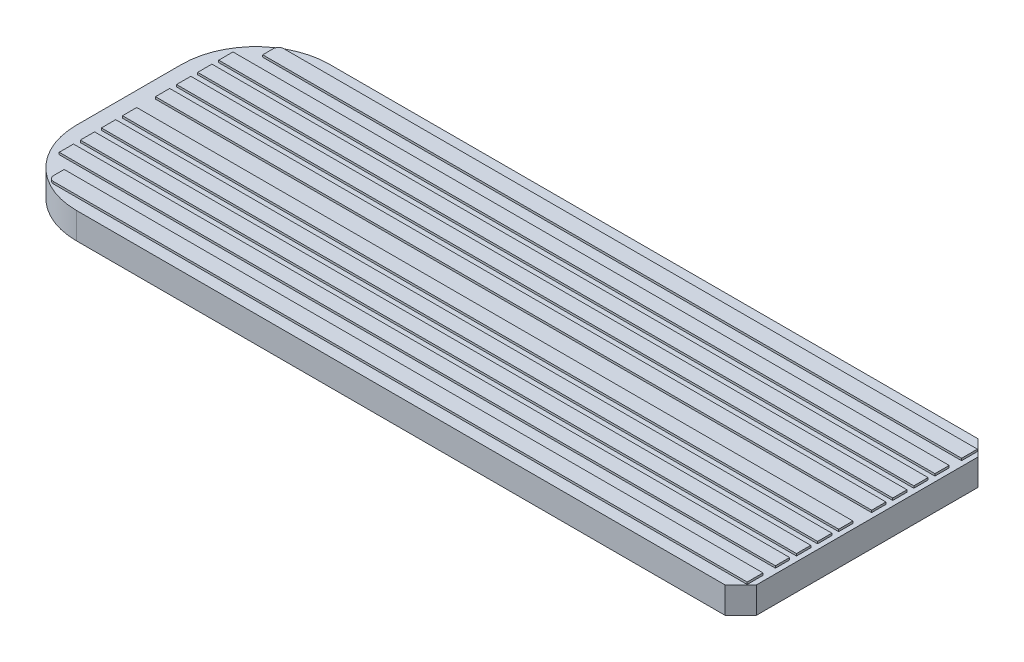
SolidWorks part; units mm, degrees
ref_plane "Front Plane" through (0, 0, 0) normal (0, 0, 1) x (1, 0, 0)
ref_plane "Top Plane" through (0, 0, 0) normal (0, 1, 0) x (1, 0, 0)
ref_plane "Right Plane" through (0, 0, 0) normal (1, 0, 0) x (0, 0, -1)
sketch "Sketch1" plane through (0, 0, 0) normal (0, 1, 0) x (1, 0, 0)
  line L0 (-55, 0) -> (55, 0) construction
  line L1 (-1400, 600) -> (1675, 600)
  line L2 (-1750, 250) -> (-1750, -250)
  line L3 (-1400, -600) -> (1675, -600)
  line L4 (1750, 525) -> (1750, -525)
  line L5 (1675, 600) -> (1750, 525)
  line L6 (1750, -525) -> (1675, -600)
  arc A0 (-1750, -250) -> (-1400, -600) centre (-1400, -250) ccw
  arc A1 (-1750, 250) -> (-1400, 600) centre (-1400, 250) cw
  point P1 (1750, -600)
  point P3 (1750, 600)
  dimension "D4" = 350
  dimension "D5" = 350
  dimension "D1" = 600
  dimension "D2" = 3500
  dimension "D3" = 1750
extrude "Boss-Extrude1" add sketch "Sketch1" along normal mid plane 125
shell "Shell1" thickness 10
sketch "Sketch2" plane through (0, 62.5, 0) normal (0, 1, 0) x (1, 0, 0)
  line L0 (-1669.4392, -311.9888) -> (-1669.4392, -244.3693)
  line L1 (-1562.1679, -545.7502) -> (1726.3596, -545.7502)
  line L2 (-1587.1679, -520.7502) -> (-1587.1679, -470.7623)
  line L3 (-1587.1679, -470.7623) -> (1726.3596, -470.7623)
  line L4 (1726.3596, -545.7502) -> (1726.3596, -470.7623)
  line L5 (-1669.4392, -411.9888) -> (1726.3596, -411.9888)
  line L6 (-1669.4392, -411.9888) -> (-1669.4392, -344.3693)
  line L7 (-1669.4392, -344.3693) -> (1726.3596, -344.3693)
  line L8 (1726.3596, -411.9888) -> (1726.3596, -344.3693)
  line L9 (-1669.4392, -311.9888) -> (1726.3596, -311.9888)
  line L10 (1726.3596, -311.9888) -> (1726.3596, -244.3693)
  line L11 (-1669.4392, -244.3693) -> (1726.3596, -244.3693)
  line L12 (-1669.4392, -211.9888) -> (-1669.4392, -144.3693)
  line L13 (-1669.4392, -211.9888) -> (1726.3596, -211.9888)
  line L14 (1726.3596, -211.9888) -> (1726.3596, -144.3693)
  line L15 (-1669.4392, -144.3693) -> (1726.3596, -144.3693)
  line L16 (-1669.4392, -111.9888) -> (-1669.4392, -44.3693)
  line L17 (-1669.4392, -111.9888) -> (1726.3596, -111.9888)
  line L18 (1726.3596, -111.9888) -> (1726.3596, -44.3693)
  line L19 (-1669.4392, -44.3693) -> (1726.3596, -44.3693)
  arc A0 (-1750, -250) -> (-1400, -600) centre (-1400, -250) ccw construction
  arc A1 (-1587.1679, -520.7502) -> (-1562.1679, -545.7502) centre (-1562.1679, -520.7502) ccw
  point P25 (-1587.1679, -545.7502)
  dimension "D2" = 25
  dimension "D1" = 4
extrude "Boss-Extrude2" add sketch "Sketch2" along normal blind 10
mirror "Mirror1" about plane through (0, 0, 0) normal (0, 0, 1) of "Boss-Extrude2"
